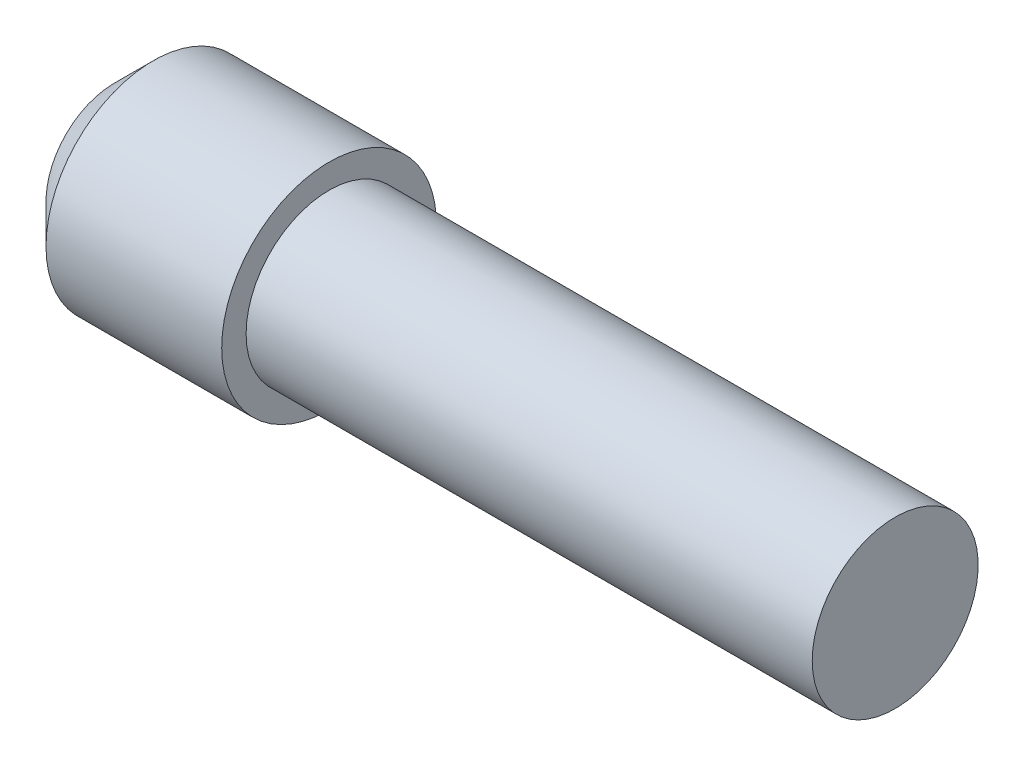
SolidWorks part; units mm, degrees
ref_plane "Front Plane" through (0, 0, 0) normal (0, 0, 1) x (1, 0, 0)
ref_plane "Top Plane" through (0, 0, 0) normal (0, 1, 0) x (1, 0, 0)
ref_plane "Right Plane" through (0, 0, 0) normal (1, 0, 0) x (0, 0, -1)
sketch "Sketch1" plane through (0, 0, 0) normal (0, 0, 1) x (1, 0, 0)
  line L0 (-9.4589, 0) -> (1.0894, 0) construction
  line L1 (0, 2.75) -> (-5.5, 2.75)
  line L2 (-5.5, 2.75) -> (-5.5, 0)
  line L3 (-5.5, 0) -> (14.5, 0)
  line L4 (0, 2.75) -> (0, 2.125)
  line L5 (0, 2.125) -> (0, 0) construction
  line L6 (0, 2.125) -> (14.5, 2.125)
  line L7 (14.5, 2.125) -> (14.5, 0)
  line L8 (9.5, 0) -> (9.5, 2.125) construction
  dimension "D1" = 9.5
  dimension "OD" = 5.5
  dimension "ID" = 4.25
  dimension "D2" = 5
  dimension "D3" = 5.5
revolve "Revolve1" add sketch "Sketch1" angle 360 about L0
chamfer "Chamfer1" distance 1 angle 45 1 edges at (-5.5, 0, 2.75)
